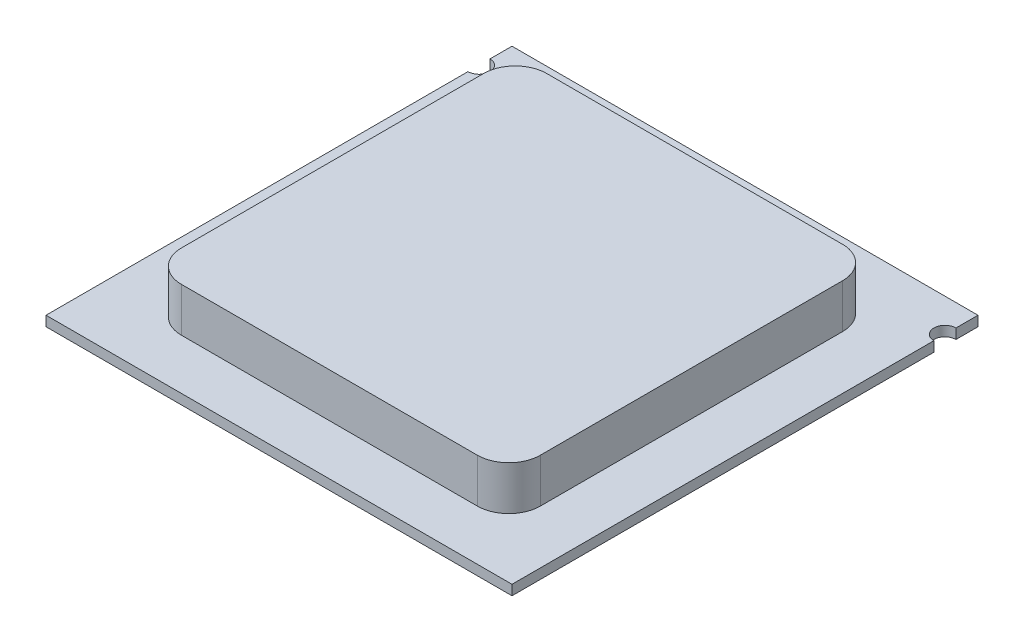
SolidWorks part; units mm, degrees
ref_plane "Front Plane" through (0, 0, 0) normal (0, 0, 1) x (1, 0, 0)
ref_plane "Top Plane" through (0, 0, 0) normal (0, 1, 0) x (1, 0, 0)
ref_plane "Right Plane" through (0, 0, 0) normal (1, 0, 0) x (0, 0, -1)
sketch "Sketch1" plane through (0, 0, 0) normal (0, 1, 0) x (1, 0, 0)
  line L0 (0, 18.5) -> (0, 0) construction
  line L1 (-18.5, 18.5) -> (18.5, 18.5)
  line L2 (-18.5, 18.5) -> (-18.5, 16.75)
  line L3 (-18.5, -18.5) -> (18.5, -18.5)
  line L4 (18.5, 18.5) -> (18.5, 16.75)
  line L5 (0, 0) -> (18.5, 0) construction
  line L6 (18.5, 15) -> (18.5, -18.5)
  line L7 (-18.5, 15) -> (-18.5, -18.5)
  arc A0 (18.5, 16.75) -> (18.5, 15) centre (18.5, 15.875) ccw
  arc A1 (-18.5, 15) -> (-18.5, 16.75) centre (-18.5, 15.875) ccw
  dimension "D4" = 0.875
  dimension "D6" = 0.875
  dimension "D1" = 37
  dimension "D2" = 37
  dimension "D3" = 1.75
  dimension "D5" = 1.75
extrude "Boss-Extrude1" add sketch "Sketch1" along normal blind 0.7937
sketch "Sketch2" plane through (0, 0.7937, 0) normal (0, 1, 0) x (1, 0, 0)
  line L0 (-14.25, 0) -> (0, 0) construction
  line L1 (-11.75, 14.5) -> (11.75, 14.5)
  line L2 (-14.25, 12) -> (-14.25, -12)
  line L3 (-11.75, -14.5) -> (11.75, -14.5)
  line L4 (14.25, 12) -> (14.25, -12)
  line L5 (0, 0) -> (0, 14.5) construction
  arc A0 (14.25, 12) -> (11.75, 14.5) centre (11.75, 12) ccw
  arc A1 (-11.75, 14.5) -> (-14.25, 12) centre (-11.75, 12) ccw
  arc A2 (-14.25, -12) -> (-11.75, -14.5) centre (-11.75, -12) ccw
  arc A3 (11.75, -14.5) -> (14.25, -12) centre (11.75, -12) ccw
  point P6 (14.25, 14.5)
  point P11 (-14.25, -14.5)
  point P14 (14.25, -14.5)
  dimension "D3" = 2.5
  dimension "D1" = 29
  dimension "D2" = 28.5
extrude "Boss-Extrude2" add sketch "Sketch2" along normal blind 3.5
